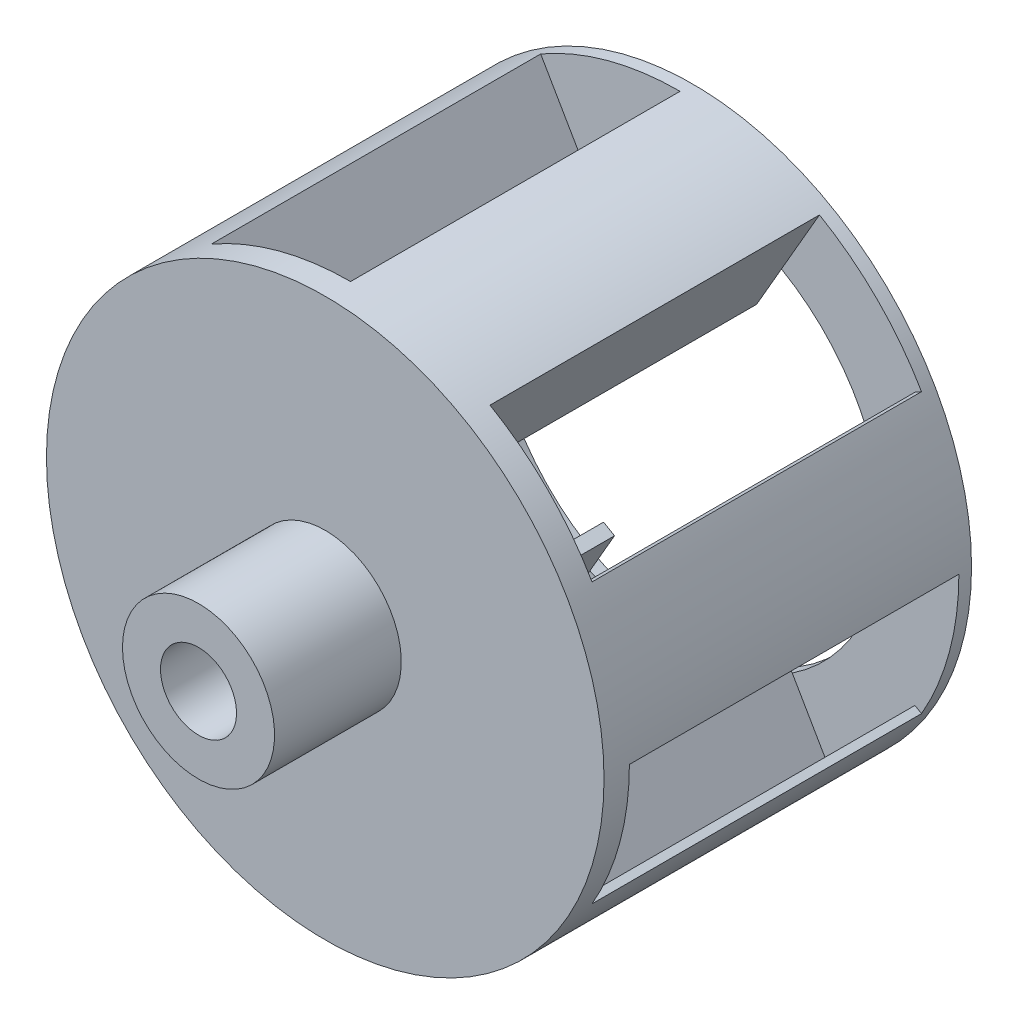
SolidWorks part; units mm, degrees
ref_plane "Front Plane" through (0, 0, 0) normal (0, 0, 1) x (1, 0, 0)
ref_plane "Top Plane" through (0, 0, 0) normal (0, 1, 0) x (1, 0, 0)
ref_plane "Right Plane" through (0, 0, 0) normal (1, 0, 0) x (0, 0, -1)
sketch "Sketch1" plane through (0, 0, 0) normal (0, 1, 0) x (1, 0, 0)
  line L0 (0, 4.3038) -> (0, -4.5382) construction
  line L1 (-7.8549, 0) -> (8.2437, 0) construction
  line L2 (5.5, 0.5) -> (0.75, 0.5)
  line L3 (0.75, 0.5) -> (0.75, -2.5)
  line L4 (0.75, -2.5) -> (1.5, -2.5)
  line L5 (1.5, -2.5) -> (1.5, 0)
  line L6 (1.5, 0) -> (5.5, 0)
  line L7 (5.5, 0) -> (5.5, 0.5)
  dimension "D1" = 1.5
  dimension "D2" = 0.75
  dimension "D3" = 0.5
  dimension "D4" = 2.5
  dimension "D5" = 5.5
revolve "Revolve1" add sketch "Sketch1" angle 360 about L0
sketch "Sketch2" plane through (0, 0, -0.5) normal (0, 0, -1) x (-1, 0, 0)
  line L0 (5.5, 0) -> (3.02, 0)
  line L1 (3.02, 0) -> (3.02, -0.25)
  line L2 (3.02, -0.25) -> (5.3442, -0.25)
  line L3 (0, 0) -> (7.9772, -4.6056) construction
  line L4 (4.6332, -2.675) -> (4.7631, -2.75)
  line L5 (2.75, -4.7631) -> (1.51, -2.6154)
  line L6 (1.51, -2.6154) -> (1.2935, -2.7404)
  line L7 (1.2935, -2.7404) -> (2.4556, -4.7532)
  line L8 (0, -5.35) -> (0, -5.5)
  line L9 (-2.75, -4.7631) -> (-1.51, -2.6154)
  line L10 (-1.51, -2.6154) -> (-1.7265, -2.4904)
  line L11 (-1.7265, -2.4904) -> (-2.8886, -4.5032)
  line L12 (-4.6332, -2.675) -> (-4.7631, -2.75)
  line L13 (-5.5, 0) -> (-3.02, 0)
  line L14 (-3.02, 0) -> (-3.02, 0.25)
  line L15 (-3.02, 0.25) -> (-5.3442, 0.25)
  line L16 (-4.6332, 2.675) -> (-4.7631, 2.75)
  line L17 (-2.75, 4.7631) -> (-1.51, 2.6154)
  line L18 (-1.51, 2.6154) -> (-1.2935, 2.7404)
  line L19 (-1.2935, 2.7404) -> (-2.4556, 4.7532)
  line L20 (0, 5.35) -> (0, 5.5)
  line L21 (2.75, 4.7631) -> (1.51, 2.6154)
  line L22 (1.51, 2.6154) -> (1.7265, 2.4904)
  line L23 (1.7265, 2.4904) -> (2.8886, 4.5032)
  line L24 (4.6332, 2.675) -> (4.7631, 2.75)
  arc A0 (4.7631, -2.75) -> (5.5, 0) centre (0, 0) ccw
  arc A1 (4.6332, -2.675) -> (5.3442, -0.25) centre (0, 0) ccw
  arc A2 (0, -5.5) -> (2.75, -4.7631) centre (0, 0) ccw
  arc A3 (0, -5.35) -> (2.4556, -4.7532) centre (0, 0) ccw
  arc A4 (-4.7631, -2.75) -> (-2.75, -4.7631) centre (0, 0) ccw
  arc A5 (-4.6332, -2.675) -> (-2.8886, -4.5032) centre (0, 0) ccw
  arc A6 (-4.7631, 2.75) -> (-5.5, 0) centre (0, 0) ccw
  arc A7 (-4.6332, 2.675) -> (-5.3442, 0.25) centre (0, 0) ccw
  arc A8 (0, 5.5) -> (-2.75, 4.7631) centre (0, 0) ccw
  arc A9 (0, 5.35) -> (-2.4556, 4.7532) centre (0, 0) ccw
  arc A10 (4.7631, 2.75) -> (2.75, 4.7631) centre (0, 0) ccw
  arc A11 (4.6332, 2.675) -> (2.8886, 4.5032) centre (0, 0) ccw
  point P42 (0, 0)
  dimension "D1" = 11
  dimension "D2" = 0.15
  dimension "D3" = 0.25
  dimension "D4" = 2.48
  dimension "D5" = 30
  dimension "D6" = 6
extrude "Boss-Extrude1" add sketch "Sketch2" along normal blind 6.5
sketch "Sketch3" plane through (0, 0, -7) normal (0, 0, -1) x (-1, 0, 0)
  circle A0 centre (0, 0) radius 5.5
  circle A1 centre (0, 0) radius 4
  dimension "D1" = 11
  dimension "D2" = 8
extrude "Boss-Extrude2" add sketch "Sketch3" along normal blind 0.25
